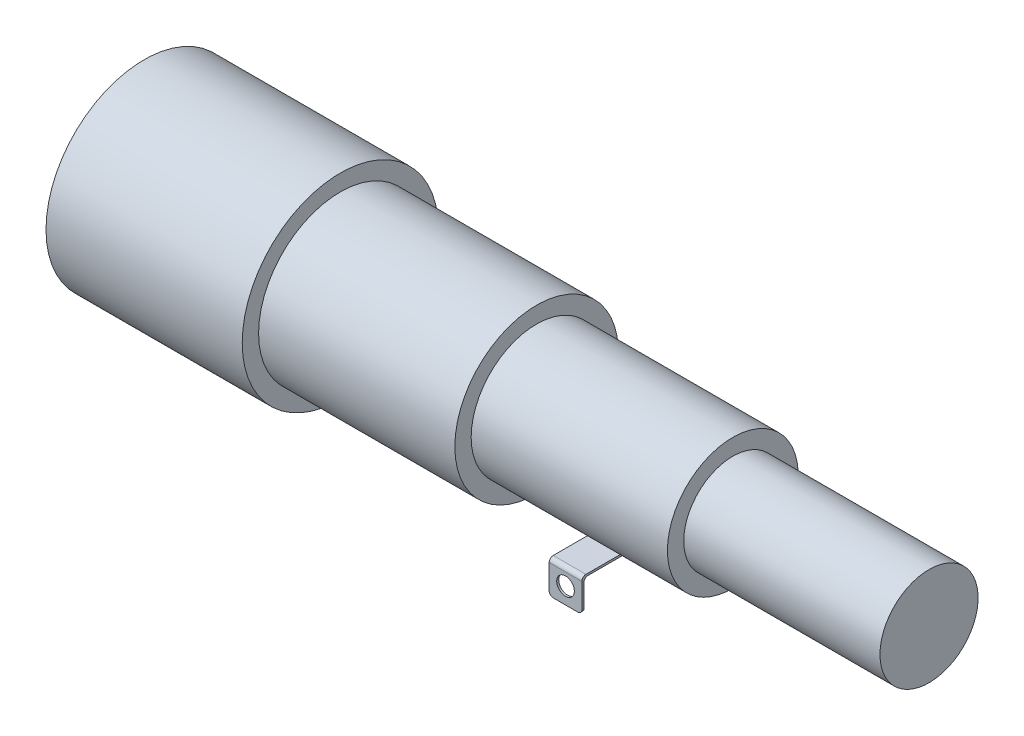
SolidWorks part; units mm, degrees
other "DetailItem10"
ref_plane "Front Plane" through (0, 0, 0) normal (0, 0, 1) x (1, 0, 0)
ref_plane "Top Plane" through (0, 0, 0) normal (0, 1, 0) x (1, 0, 0)
ref_plane "Right Plane" through (0, 0, 0) normal (1, 0, 0) x (0, 0, -1)
sketch "Sketch1" plane through (0, 0, 0) normal (1, 0, 0) x (0, 0, -1)
  circle A0 centre (0, 0) radius 152.4
  dimension "D1" = 304.8
extrude "Boss-Extrude1" add sketch "Sketch1" along normal blind 304.8 contours A0
sketch "Sketch2" plane through (304.8, 0, 0) normal (1, 0, 0) x (0, 0, -1)
  circle A0 centre (0, 0) radius 127
  dimension "D1" = 254
extrude "Boss-Extrude2" add sketch "Sketch2" along normal blind 304.8
sketch "Sketch3" plane through (609.6, 0, 0) normal (1, 0, 0) x (0, 0, -1)
  circle A0 centre (0, 0) radius 101.6
  dimension "D1" = 203.2
extrude "Boss-Extrude3" add sketch "Sketch3" along normal blind 304.8
sketch "Sketch4" plane through (914.4, 0, 0) normal (1, 0, 0) x (0, 0, -1)
  circle A0 centre (0, 0) radius 76.2
  dimension "D1" = 152.4
extrude "Boss-Extrude4" add sketch "Sketch4" along normal blind 304.8
sketch "Sketch5" plane through (0, 0, 0) normal (0, 0, 1) x (1, 0, 0)
  line L1 (756.033, 292.8121) -> (756.033, -186.6588) construction
  line L2 (609.6, -101.6) -> (914.4, -101.6) construction
  line L3 (609.6, -101.6) -> (914.4, -101.6) construction
  line L4 (730.633, -101.6) -> (781.433, -101.6)
  line L5 (730.633, -101.6) -> (730.633, -104.775)
  line L6 (730.633, -104.775) -> (781.433, -104.775)
  line L7 (781.433, -104.775) -> (781.433, -101.6)
  point P7 (756.033, -101.6)
  point P11 (756.033, -101.6)
  dimension "D1" = 50.8
  dimension "D2" = 3.175
sketch3d "3DSketch2"
  line L0 (756.033, 292.8121, 0) -> (756.033, -186.6588, 0) construction
sketch "Sketch6" plane through (756.033, 0, 0) normal (-1, 0, 0) x (0, 0, 1)
  line L0 (101.473, -101.6) -> (-101.473, -101.6)
  line L2 (-101.473, -101.6) -> (-101.473, -152.4)
  line L3 (101.473, -101.6) -> (101.473, -152.4)
  line L4 (98.298, -104.775) -> (-98.298, -104.775)
  line L5 (-98.298, -104.775) -> (-98.298, -152.4)
  line L6 (-98.298, -152.4) -> (-101.473, -152.4)
  line L7 (98.298, -104.775) -> (98.298, -152.4)
  line L8 (98.298, -152.4) -> (101.473, -152.4)
  point P4 (0, -101.6)
  dimension "D1" = 202.946
  dimension "D2" = 3.175
  dimension "D3" = 3.175
  dimension "D4" = 3.175
  dimension "D5" = 50.8
extrude "Boss-Extrude6" add sketch "Sketch6" along normal mid plane 50.8 separate body
fillet "Fillet1" radius 6.35 8 edges at (781.433, -152.4, -99.8855) (781.433, -152.4, 99.8855) (730.633, -152.4, -99.8855) (730.633, -152.4, 99.8855) (756.033, -104.775, -98.298) (756.033, -101.6, -101.473) (756.033, -101.6, 101.473) (756.033, -104.775, 98.298)
sketch "Sketch7" plane through (0, 0, 101.473) normal (0, 0, 1) x (1, 0, 0)
  line L0 (756.033, -152.4) -> (756.033, -52.9505) construction
  line L1 (736.983, -152.4) -> (775.083, -152.4) construction
  circle A0 centre (756.033, -127) radius 13.716
  dimension "D2" = 27.432
  dimension "D1" = 25.4
extrude "Cut-Extrude1" cut sketch "Sketch7" against normal through all both and the other way through all
